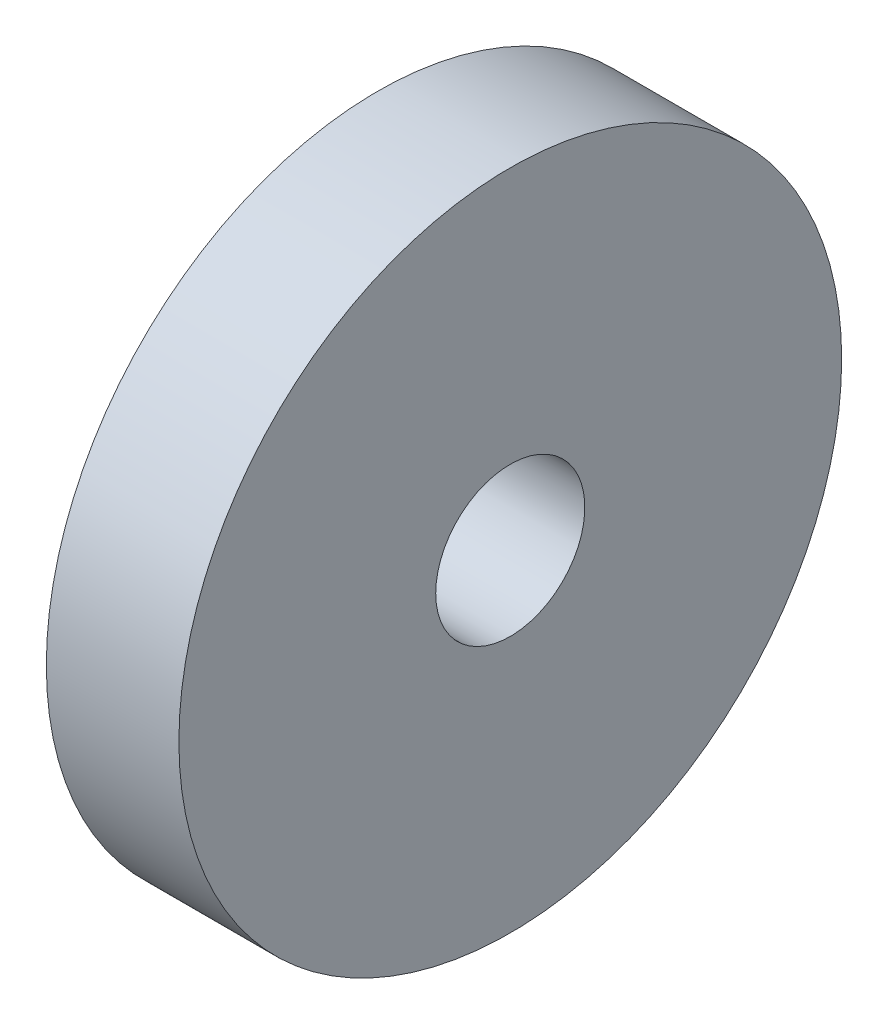
SolidWorks part; units mm, degrees
ref_plane "Front Plane" through (0, 0, 0) normal (0, 0, 1) x (1, 0, 0)
ref_plane "Top Plane" through (0, 0, 0) normal (0, 1, 0) x (1, 0, 0)
ref_plane "Right Plane" through (0, 0, 0) normal (1, 0, 0) x (0, 0, -1)
sketch "Sketch1" plane through (0, 0, 0) normal (1, 0, 0) x (0, 0, -1)
  circle A0 centre (0, 0) radius 10
extrude "Boss-Extrude1" add sketch "Sketch1" along normal blind 8
sketch "Sketch2" plane through (8, 0, 0) normal (1, 0, 0) x (0, 0, -1)
  circle A0 centre (0, 0) radius 13.5
extrude "Cut-Extrude1" cut sketch "Sketch2" against normal blind 2
sketch "Sketch3" plane through (0, 0, 0) normal (-1, 0, 0) x (0, 0, 1)
  circle A0 centre (0, 0) radius 13.5
extrude "Cut-Extrude2" cut sketch "Sketch3" against normal blind 2
sketch "Sketch4" plane through (2, 0, 0) normal (-1, 0, 0) x (0, 0, 1)
  circle A0 centre (0, 0) radius 2.25
extrude "Cut-Extrude3" cut sketch "Sketch4" against normal through all both and the other way through all
